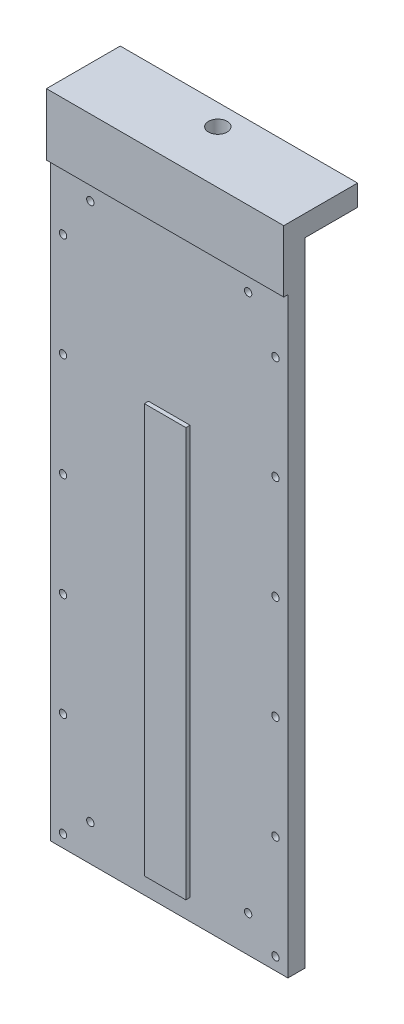
SolidWorks part; units mm, degrees
ref_plane "Front Plane" through (0, 0, 0) normal (0, 0, 1) x (1, 0, 0)
ref_plane "Top Plane" through (0, 0, 0) normal (0, 1, 0) x (1, 0, 0)
ref_plane "Right Plane" through (0, 0, 0) normal (1, 0, 0) x (0, 0, -1)
sketch "Sketch1" plane through (0, 0, 0) normal (0, 1, 0) x (1, 0, 0)
  line L1 (-28.575, -2.54) -> (28.575, -2.54)
  line L2 (-28.575, -2.54) -> (-28.575, 2.54)
  line L3 (-28.575, 2.54) -> (28.575, 2.54)
  line L4 (28.575, -2.54) -> (28.575, 2.54)
  line L5 (-28.575, -2.54) -> (28.575, 2.54) construction
  line L6 (-28.575, 2.54) -> (28.575, -2.54) construction
  point P0 (0, 0)
  dimension "D1" = 57.15
  dimension "D2" = 5.08
extrude "Boss-Extrude1" add sketch "Sketch1" against normal blind 152.4
sketch "Sketch2" plane through (0, 0, 2.54) normal (0, 0, 1) x (1, 0, 0)
  line L0 (-5, -152.4) -> (-5, -53.9)
  line L1 (-28.575, -152.4) -> (28.575, -152.4) construction
  line L2 (-5, -53.9) -> (5, -53.9)
  line L3 (5, -53.9) -> (5, -152.4)
  line L4 (5, -152.4) -> (28.575, -152.4)
  line L5 (28.575, -152.4) -> (28.575, -14.9)
  line L6 (28.575, -152.4) -> (28.575, 0) construction
  line L7 (28.575, -14.9) -> (-28.575, -14.9)
  line L8 (-28.575, -152.4) -> (-28.575, 0) construction
  line L9 (-28.575, -14.9) -> (-28.575, -152.4)
  line L10 (-28.575, -152.4) -> (-5, -152.4)
  line L11 (0, -152.4) -> (0, 0) construction
  point P21 (0, -53.9)
  dimension "D1" = 10
  dimension "D2" = 98.5
  dimension "D3" = 137.5
extrude "Cut-Extrude1" cut sketch "Sketch2" against normal blind 1
sketch "Sketch3" plane through (0, 0, -2.54) normal (0, 0, -1) x (-1, 0, 0)
  line L0 (28.575, -152.4) -> (28.575, 0) construction
  line L1 (-28.575, 0) -> (28.575, 0)
  line L2 (-28.575, 0) -> (-28.575, -5.08)
  line L3 (-28.575, -5.08) -> (28.575, -5.08)
  line L4 (28.575, 0) -> (28.575, -5.08)
  dimension "D1" = 5.08
extrude "Boss-Extrude2" add sketch "Sketch3" along normal blind 12.7
sketch "Sketch4" plane through (0, 0, 0) normal (0, 1, 0) x (1, 0, 0)
  line L0 (0, 15.24) -> (0, -2.54) construction
  line L1 (-28.575, 15.24) -> (28.575, 15.24) construction
  line L2 (-28.575, -2.54) -> (28.575, -2.54) construction
  circle A0 centre (0, 10.16) radius 2.25
  dimension "D1" = 4.5
  dimension "D2" = 5.08
extrude "Cut-Extrude2" cut sketch "Sketch4" against normal blind 12.7
sketch "Sketch5" plane through (0, 0, 1.54) normal (0, 0, 1) x (1, 0, 0)
  line L0 (0, -152.4) -> (0, -14.9) construction
  line L1 (-5, -152.4) -> (5, -152.4) construction
  line L2 (28.575, -14.9) -> (-28.575, -14.9) construction
  line L3 (5, -152.4) -> (28.575, -152.4) construction
  line L4 (-19, -148.65) -> (19, -148.65) construction
  line L5 (-19, -148.65) -> (-19, -19.15) construction
  line L6 (-19, -19.15) -> (19, -19.15) construction
  line L7 (19, -148.65) -> (19, -19.15) construction
  line L8 (-19, -148.65) -> (19, -19.15) construction
  line L9 (-19, -19.15) -> (19, -148.65) construction
  circle A0 centre (-19, -19.15) radius 0.889
  circle A1 centre (19, -19.15) radius 0.889
  circle A2 centre (-19, -148.65) radius 0.889
  circle A3 centre (19, -148.65) radius 0.889
  point P6 (0, -83.9)
  dimension "D1" = 1.778
  dimension "D2" = 1.778
  dimension "D3" = 1.778
  dimension "D4" = 1.778
  dimension "D5" = 38
  dimension "D6" = 3.75
  dimension "D7" = 129.5
extrude "Cut-Extrude3" cut sketch "Sketch5" against normal through all
sketch "Sketch6" plane through (0, -152.4, 0) normal (0, -1, 0) x (1, 0, 0)
  line L1 (-28.575, -2.54) -> (28.575, -2.54)
  line L2 (-28.575, -2.54) -> (-28.575, 1.54)
  line L3 (-28.575, 1.54) -> (28.575, 1.54)
  line L4 (28.575, -2.54) -> (28.575, 1.54)
extrude "Boss-Extrude3" add sketch "Sketch6" along normal blind 5
sketch "Sketch7" plane through (0, 0, 1.54) normal (0, 0, 1) x (1, 0, 0)
  line L0 (28.575, -157.4) -> (-28.575, -157.4) construction
  line L3 (-28.575, -14.9) -> (-28.575, -157.4) construction
  circle A0 centre (-25.575, -154.4) radius 0.889
  dimension "D1" = 1.778
  dimension "D2" = 3
  dimension "D3" = 3
extrude "Cut-Extrude4" cut sketch "Sketch7" against normal through all
mirror "Mirror1" about plane through (0, 0, 0) normal (1, 0, 0) of "Cut-Extrude4"
pattern_linear "LPattern1" count 6 spacing 25 along (0, 1, 0) of "Mirror1", "Cut-Extrude4"
